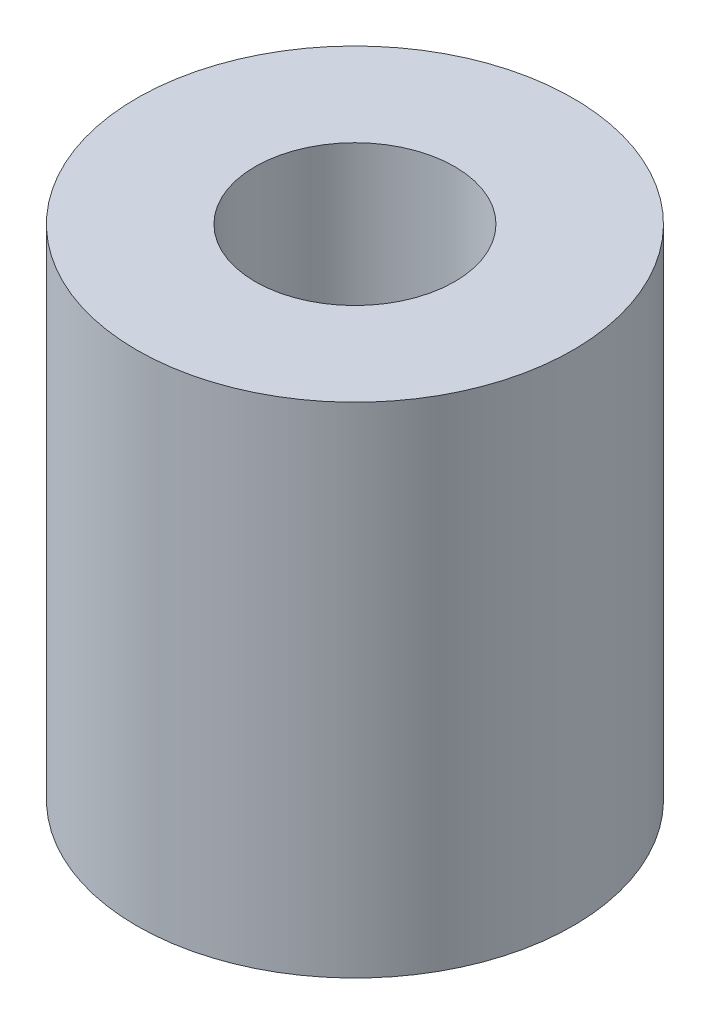
SolidWorks part; units mm, degrees
material "Brass"
ref_plane "Front Plane" through (0, 0, 0) normal (0, 0, 1) x (1, 0, 0)
ref_plane "Top Plane" through (0, 0, 0) normal (0, 1, 0) x (1, 0, 0)
ref_plane "Right Plane" through (0, 0, 0) normal (1, 0, 0) x (0, 0, -1)
sketch "Sketch1" plane through (0, 0, 0) normal (0, 1, 0) x (1, 0, 0)
  circle A0 centre (0, 0) radius 1.75
  dimension "D1" = 3.5
extrude "Boss-Extrude1" add sketch "Sketch1" along normal blind 4
hole_wizard "M2x0.4 Tapped Hole1" positions "Sketch2" profile "Sketch3" tap size "M2x0.4" standard "ANSI Metric" end condition through all
sketch "Sketch2" plane through (0, 4, 0) normal (0, 1, 0) x (1, 0, 0)
  point P0 (0, 0)
cosmetic thread "Hole Thread1"
sketch "Sketch3" plane through (0, 4, 0) normal (1, 0, 0) x (0, 0, 1)
  line L0 (0, 0) -> (0, 4)
  line L1 (0, 4) -> (0.8, 4)
  line L2 (0.8, 4) -> (0.8, 0)
  line L5 (0.8, 0) -> (0, 0)
  line L11 (0, -6.35) -> (0, 107.95) construction
  dimension "Thru Tap Drill Dia." = 1.6
  dimension "Thru Tap Drill Depth" = 4
